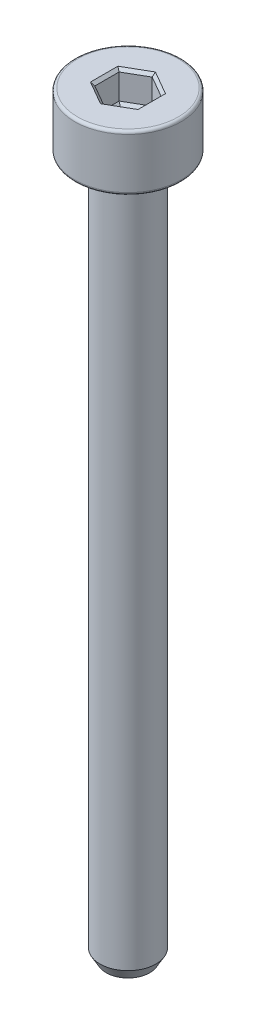
SolidWorks part; units mm, degrees
material "AISI Type A2 Tool Steel"
ref_plane "Front Plane" through (0, 0, 0) normal (0, 0, 1) x (1, 0, 0)
ref_plane "Top Plane" through (0, 0, 0) normal (0, 1, 0) x (1, 0, 0)
ref_plane "Right Plane" through (0, 0, 0) normal (1, 0, 0) x (0, 0, -1)
sketch "Sketch1" plane through (0, 0, 0) normal (0, 1, 0) x (1, 0, 0)
  circle A0 centre (0, 0) radius 1
  dimension "D1" = 2
extrude "Boss-Extrude1" add sketch "Sketch1" along normal blind 25
sketch "Sketch2" plane through (0, 25, 0) normal (0, 1, 0) x (1, 0, 0)
  circle A0 centre (0, 0) radius 1.9
  dimension "D1" = 3.8
extrude "Boss-Extrude2" add sketch "Sketch2" along normal blind 2
sketch "Sketch3" plane through (0, 27, 0) normal (0, 1, 0) x (1, 0, 0)
  line L1 (0, 0.866) -> (-0.75, 0.433)
  line L2 (-0.75, 0.433) -> (-0.75, -0.433)
  line L3 (-0.75, -0.433) -> (0, -0.866)
  line L4 (0, -0.866) -> (0.75, -0.433)
  line L5 (0.75, -0.433) -> (0.75, 0.433)
  line L6 (0.75, 0.433) -> (0, 0.866)
  circle A0 centre (0, 0) radius 0.75 construction
  dimension "D1" = 1.5
extrude "Cut-Extrude1" cut sketch "Sketch3" against normal blind 1
fillet "Fillet1" radius 0.1 2 edges at (0, 25, 1.9) (0, 27, 1.9)
chamfer "Chamfer1" distance 0.1 angle 45 1 edges at (0, 0, 1)
sketch "Sketch4" plane through (0, 0, 0) normal (0, 0, 1) x (1, 0, 0)
  line L0 (0, 0) -> (0, 0.158) construction
  line L1 (0, 0) -> (1.01, 0) construction
  line L3 (1.01, 0) -> (1.01, 0.4)
  line L4 (1.01, 0.4) -> (0.7791, 0)
  line L5 (0.7791, 0) -> (1.01, 0)
  dimension "D1" = 1.01
  dimension "D2" = 60
  dimension "D3" = 0.4
revolve "Cut-Revolve1" cut sketch "Sketch4" angle 360 about L0
chamfer "Chamfer2" distance 0.1 angle 45 6 edges at (-0.75, 27, 0) (-0.375, 27, 0.6495) (0.375, 27, 0.6495) (0.75, 27, 0) (0.375, 27, -0.6495) (-0.375, 27, -0.6495)
sketch "Sketch6" plane through (0, 26, 0) normal (0, 1, 0) x (1, 0, 0)
  line L1 (0, 0.866) -> (-0.75, 0.433)
  line L2 (-0.75, 0.433) -> (-0.75, -0.433)
  line L3 (-0.75, -0.433) -> (0, -0.866)
  line L4 (0, -0.866) -> (0.75, -0.433)
  line L5 (0.75, -0.433) -> (0.75, 0.433)
  line L6 (0.75, 0.433) -> (0, 0.866)
  circle A0 centre (0, 0) radius 0.75 construction
extrude "Cut-Extrude2" cut sketch "Sketch6" against normal blind 0.1 draft 45
